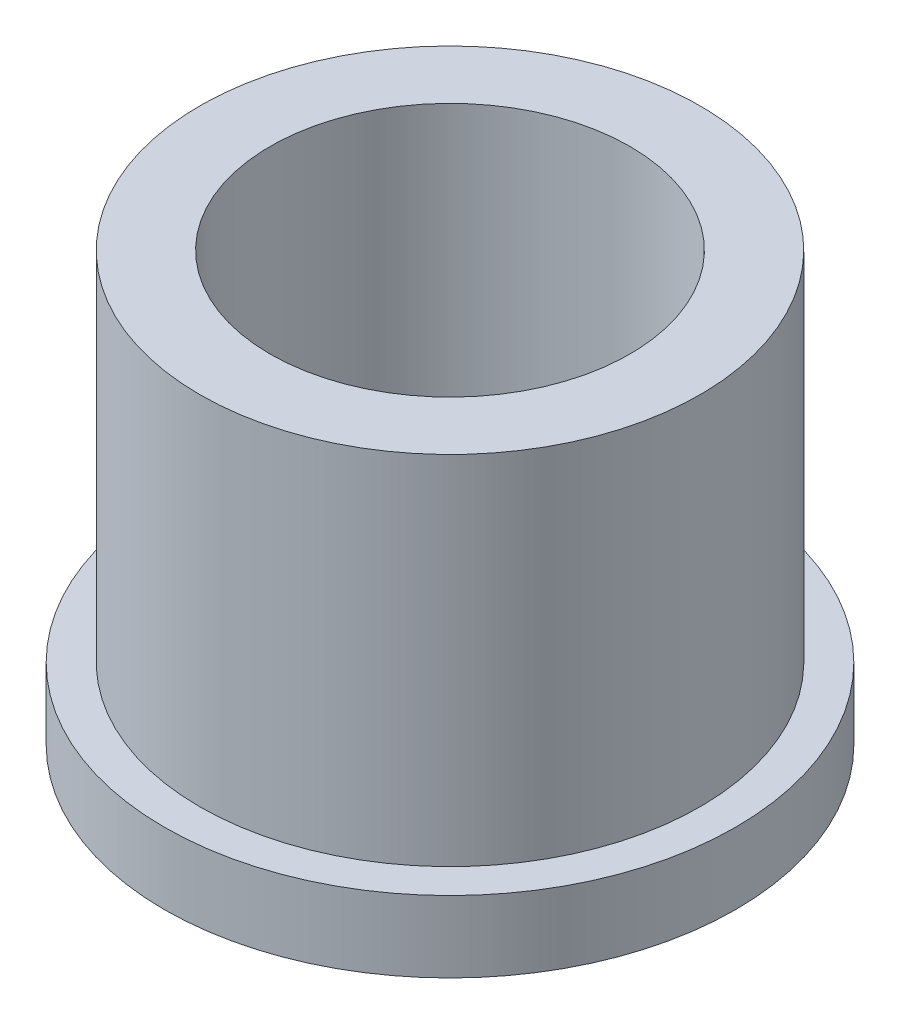
SolidWorks part; units mm, degrees
ref_plane "Front" through (0, 0, 0) normal (0, 0, 1) x (1, 0, 0)
ref_plane "Top" through (0, 0, 0) normal (0, 1, 0) x (1, 0, 0)
ref_plane "Right" through (0, 0, 0) normal (1, 0, 0) x (0, 0, -1)
sketch "Sketch1" plane through (0, 0, 0) normal (0, 1, 0) x (1, 0, 0)
  circle A0 centre (0, 0) radius 8.001
  circle A1 centre (0, 0) radius 11.1252
  circle A2 centre (0, 0) radius 12.7
  dimension "ID" = 16.002
  dimension "OD" = 22.2504
  dimension "Flange OD" = 25.4
sketch "Sketch2" plane through (0, 0, 0) normal (1, 0, 0) x (0, 0, -1)
  line L0 (0, 0) -> (0, 9.525) construction
  line L1 (0, 0) -> (0, -9.525) construction
  line L2 (0, 9.525) -> (8.001, 9.525) construction
  line L3 (0, 9.525) -> (-8.001, 9.525) construction
  line L4 (8.001, 9.525) -> (8.001, 0) construction
  line L5 (8.001, 0) -> (8.001, -9.525) construction
  line L6 (8.001, -9.525) -> (0, -9.525) construction
  line L7 (-8.001, 9.525) -> (-8.001, 0) construction
  line L8 (-8.001, 0) -> (-8.001, -9.525) construction
  line L9 (-8.001, -9.525) -> (0, -9.525) construction
  line L10 (8.001, 0) -> (-8.001, 0) construction
  line L11 (8.001, -9.525) -> (12.7, -9.525) construction
  line L12 (12.7, -9.525) -> (12.7, 0) construction
  line L15 (8.001, 9.525) -> (11.1252, 9.525) construction
  line L16 (11.1252, 9.525) -> (11.1252, 0) construction
  point P3 (0, -6.35)
  point P22 (-8.001, 9.525)
  dimension "Flange Thickness" = 3.175
  dimension "Length" = 19.05
sketch "Sketch3" plane through (0, 0, 0) normal (0, 1, 0) x (1, 0, 0)
  circle A0 centre (0, 0) radius 8.001 construction
  circle A1 centre (0, 0) radius 11.1252 construction
  circle A2 centre (0, 0) radius 8.001
  circle A3 centre (0, 0) radius 11.1252
extrude "Boss-Extrude1" add sketch "Sketch3" along normal up to vertex (9.525 mm away) and the other way up to vertex (9.525 mm away) up to point (0, 9.525, 0) other way up to point (0, -9.525, 0)
sketch "Sketch6" plane through (0, 0, 0) normal (0, 1, 0) x (1, 0, 0)
  circle A0 centre (0, 0) radius 12.7 construction
  circle A1 centre (0, 0) radius 11.1252 construction
  circle A2 centre (0, 0) radius 12.7
  circle A3 centre (0, 0) radius 11.1252
extrude "Boss-Extrude2" add sketch "Sketch6" along normal up to vertex (-6.35 mm away) from vertex at -9.525 starting at point (0, -9.525, 0)
sketch "Sketch5" plane through (0, 0, 0) normal (1, 0, 0) x (0, 0, -1)
  point P0 (11.1252, 9.525)
  point P1 (12.7, -9.525)
  dimension "D1" = 19.05
